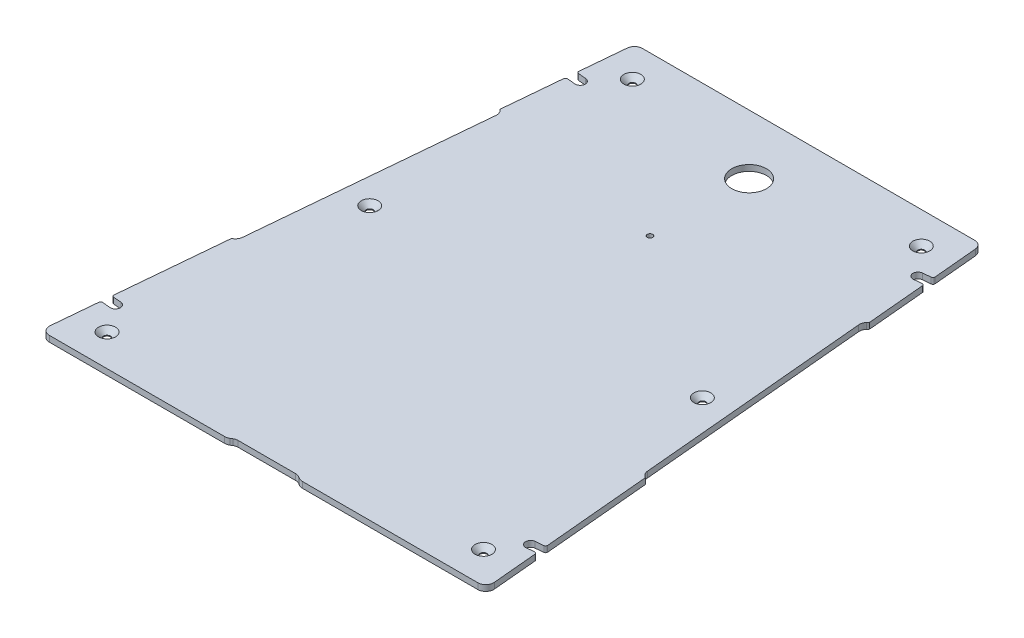
SolidWorks part; units mm, degrees
ref_plane "Front Plane" through (0, 0, 0) normal (0, 0, 1) x (1, 0, 0)
ref_plane "Top Plane" through (0, 0, 0) normal (0, 1, 0) x (1, 0, 0)
ref_plane "Right Plane" through (0, 0, 0) normal (1, 0, 0) x (0, 0, -1)
sketch "Sketch1" plane through (0, 0, 0) normal (0, 1, 0) x (1, 0, 0)
  line L0 (-175, 275) -> (-225, -275)
  line L1 (-225, -275) -> (225, -275)
  line L2 (225, -275) -> (175, 275)
  line L3 (175, 275) -> (-175, 275)
  line L4 (0, -275) -> (0, 275) construction
  line L5 (-200, 0) -> (200, 0) construction
  line L6 (-145.7771, 243) -> (-189.9589, -243) construction
  line L7 (-189.9589, -243) -> (189.9589, -243) construction
  line L8 (189.9589, -243) -> (145.7771, 243) construction
  line L9 (145.7771, 243) -> (-145.7771, 243) construction
  circle A0 centre (0, 215) radius 17.5
  circle A1 centre (-145.7771, 243) radius 3.4
  circle A2 centre (145.7771, 243) radius 3.4
  circle A5 centre (-189.9589, -243) radius 3.4
  circle A6 centre (189.9589, -243) radius 3.4
  circle A7 centre (-167.868, 0) radius 3.4
  circle A8 centre (167.868, 0) radius 3.4
  circle A9 centre (0, 115) radius 2.731
  point P8 (0, 0)
  point P12 (0, 0)
  dimension "D3" = 35
  dimension "D5" = 6.8
  dimension "D8" = 6.8
  dimension "D12" = 5.4621
  dimension "D1" = 350
  dimension "D2" = 550
  dimension "D4" = 60
  dimension "D10" = 450
  dimension "D11" = 100
  dimension "D13" = 32
extrude "Boss-Extrude1" add sketch "Sketch1" against normal blind 6
fillet "Fillet1" radius 8 4 edges at (225, -3, 275) (-225, -3, 275) (175, -3, -275) (-175, -3, -275)
extrude "Cut-Extrude4" cut sketch "Sketch5" against normal blind 20
sketch "Sketch5" plane through (0, 0, 377.3339) normal (0, 1, 0) x (0, 0, 1)
  line L0 (-592.3339, 0) -> (-592.3339, 41) construction
  line L1 (-592.3339, 0) -> (-520.1613, 72.1726) construction
  circle A7 centre (-563.3425, 28.9914) radius 3.4
  circle A8 centre (-563.3425, -28.9914) radius 3.4
  circle A9 centre (-621.3253, -28.9914) radius 3.4
  circle A10 centre (-621.3253, 28.9914) radius 3.4
  point P12 (-592.3339, 0)
  point P13 (-539.2171, 0)
  point P14 (-592.3339, 0)
  point P15 (-514.4105, -0.115)
  point P19 (-592.3339, 0)
  dimension "D3" = 6.8
  dimension "D2" = 45
  dimension "D4" = 41
  dimension "D5" = 4
sketch "Sketch6" plane through (0, 0, 0) normal (0, 1, 0) x (1, 0, 0)
  line L0 (0, 275) -> (0, -275) construction
  line L1 (167.6943, 275) -> (-167.6943, 275) construction
  line L2 (-216.2397, -275) -> (216.2397, -275) construction
  line L3 (199.9342, 0.7243) -> (-199.9342, 0.7243) construction
  line L4 (224.2069, -266.2757) -> (175.6614, 267.7243) construction
  line L5 (-175.6614, 267.7243) -> (-224.2069, -266.2757) construction
  line L6 (-204.632, -95.1331) -> (-182.7223, 145.8731)
  line L7 (-204.632, -95.1331) -> (-218.4599, -106.6564)
  line L8 (-182.7223, 145.8731) -> (-194.2456, 159.7011)
  line L9 (-218.4599, -106.6564) -> (-194.2456, 159.7011)
  point P13 (-124.3469, 2.1706)
  dimension "D1" = 18
  dimension "D2" = 242
  dimension "D3" = 135
  dimension "D4" = 4
extrude "Cut-Extrude5" cut sketch "Sketch6" against normal blind 10
sketch "Sketch7" plane through (0, 0, 0) normal (0, 1, 0) x (1, 0, 0)
  line L0 (0, 275) -> (0, -275) construction
  line L1 (167.6943, 275) -> (-167.6943, 275) construction
  line L2 (-216.2397, -275) -> (216.2397, -275) construction
  line L4 (-31.3206, -271.5943) -> (31.3206, -271.5943)
  line L5 (-31.3206, -271.5943) -> (-45, -279.8932)
  line L6 (-45, -279.8932) -> (45, -279.8932)
  line L7 (31.3206, -271.5943) -> (45, -279.8932)
  line L8 (-31.3206, -271.5943) -> (45, -279.8932) construction
  line L9 (-45, -279.8932) -> (31.3206, -271.5943) construction
  dimension "D1" = 90
  dimension "D2" = 16
extrude "Cut-Extrude6" cut sketch "Sketch7" against normal blind 10
mirror "Mirror2" about plane through (0, 0, 0) normal (1, 0, 0) of "Cut-Extrude5"
fillet "Fillet2" radius 8 8 edges at (-204.632, -3, 95.1331) (-182.7223, -3, -145.8731) (-36.9344, -3, 275) (-31.3206, -3, 271.5943) (36.9344, -3, 275) (31.3206, -3, 271.5943) (204.632, -3, 95.1331) (182.7223, -3, -145.8731)
chamfer "Chamfer1" distance 5.15 angle 45 6 edges at (-145.7771, 0, -239.6) (189.9589, 0, 239.6) (167.868, 0, -3.4) (-189.9589, 0, 246.4) (-167.868, 0, 3.4) (145.7771, 0, -246.4)
sketch "Sketch9" plane through (0, 0, 0) normal (0, 1, 0) x (1, 0, 0)
  line L0 (0, 275) -> (0, -271.5943) construction
  line L1 (167.6943, 275) -> (-167.6943, 275) construction
  line L2 (29.0836, -271.5943) -> (-29.0836, -271.5943) construction
  line L3 (-193.6771, 25.37) -> (193.6771, 25.37) construction
  line L4 (-204.332, -91.833) -> (-183.0223, 142.573) construction
  line L5 (204.332, -91.833) -> (183.0223, 142.573) construction
  line L6 (-148.0781, 29.9183) -> (-163.4505, -139.1782)
  line L7 (-200.9499, -54.63) -> (200.9499, -54.63) construction
  line L8 (-123.1808, 52.6549) -> (123.1808, 52.6549)
  line L9 (-138.5532, -166.4416) -> (138.5532, -166.4416)
  line L10 (148.0781, 29.9183) -> (163.4505, -139.1782)
  arc A0 (-163.4505, -139.1782) -> (-138.5532, -166.4416) centre (-138.5532, -141.4416) ccw
  arc A1 (-148.0781, 29.9183) -> (-123.1808, 52.6549) centre (-123.1808, 27.6549) cw
  arc A2 (163.4505, -139.1782) -> (138.5532, -166.4416) centre (138.5532, -141.4416) cw
  arc A3 (148.0781, 29.9183) -> (123.1808, 52.6549) centre (123.1808, 27.6549) ccw
  point P14 (-155.7643, -54.63)
  point P21 (-165.929, -166.4416)
  point P24 (-146.0111, 52.6549)
  point P28 (0, -166.4416)
  point P31 (0, 52.6549)
  dimension "D4" = 25
  dimension "D1" = 45
  dimension "D2" = 80
  dimension "D3" = 220
sketch "Sketch10" [suppressed] plane through (0, 0, 94.4754) normal (0, 0, 1) x (1, 0, 0)
  line L0 (-89.3279, 30) -> (-81.3279, 30)
  line L1 (-144.5624, 30) -> (-37.7732, 30) construction
  arc A0 (-89.3279, 30) -> (-81.3279, 30) centre (-85.3279, 33) ccw
  point P5 (-85.3279, 30)
  dimension "D1" = 10
sweep "Cut-Sweep2" [suppressed] cut profiles "Sketch10" path "Sketch9"
sketch "Sketch11" plane through (0, 0, 0) normal (0, 1, 0) x (1, 0, 0)
  line L3 (167.6943, 275) -> (-167.6943, 275) construction
  line L4 (-179.9105, 220.9844) -> (-169.9516, 220.0791)
  line L5 (-219.0014, -209.0156) -> (-209.0425, -209.9209)
  line L6 (-219.9249, -219.1737) -> (-209.9659, -220.0791)
  line L7 (-175.6614, 267.7243) -> (-186.3437, 150.2188) construction
  line L8 (-180.834, 210.8263) -> (-170.875, 209.9209)
  line L9 (-179.9105, 220.9844) -> (-180.834, 210.8263)
  line L10 (-219.0014, -209.0156) -> (-219.9249, -219.1737)
  line L11 (-208.9777, -98.7545) -> (-224.2069, -266.2757) construction
  line L12 (-216.2397, -275) -> (-39.1713, -275) construction
  line L13 (0, -3.3) -> (0, 3.3) construction
  line L14 (219.0014, -209.0156) -> (219.9249, -219.1737)
  line L15 (179.9105, 220.9844) -> (180.834, 210.8263)
  line L16 (180.834, 210.8263) -> (170.875, 209.9209)
  line L17 (219.9249, -219.1737) -> (209.9659, -220.0791)
  line L18 (219.0014, -209.0156) -> (209.0425, -209.9209)
  line L19 (179.9105, 220.9844) -> (169.9516, 220.0791)
  arc A1 (-170.875, 209.9209) -> (-169.9516, 220.0791) centre (-170.4133, 215) ccw
  arc A3 (-209.9659, -220.0791) -> (-209.0425, -209.9209) centre (-209.5042, -215) ccw
  arc A4 (209.9659, -220.0791) -> (209.0425, -209.9209) centre (209.5042, -215) cw
  arc A5 (170.875, 209.9209) -> (169.9516, 220.0791) centre (170.4133, 215) cw
  dimension "D1" = 5.1
  dimension "D4" = 10
  dimension "D2" = 10
  dimension "D3" = 60
  dimension "D5" = 60
extrude "Cut-Extrude7" cut sketch "Sketch11" against normal blind 10
fillet "Fillet3" radius 2 8 edges at (180.834, -3, -210.8263) (179.9105, -3, -220.9844) (219.0014, -3, 209.0156) (219.9249, -3, 219.1737) (-219.9249, -3, 219.1737) (-219.0014, -3, 209.0156) (-180.834, -3, -210.8263) (-179.9105, -3, -220.9844)
sketch "Sketch12" plane through (0, 0, 0) normal (0, 1, 0) x (1, 0, 0)
  line L0 (75, 275) -> (75, 155) construction
  line L1 (167.6943, 275) -> (-167.6943, 275) construction
  line L3 (0, -3.3) -> (0, 3.3) construction
  circle A0 centre (75, 175) radius 2.6
  circle A1 centre (75, 155) radius 2.6
  dimension "D1" = 5.2
  dimension "D2" = 20
  dimension "D3" = 100
  dimension "D4" = 75
extrude "Cut-Extrude8" [suppressed] cut sketch "Sketch12" against normal up to next
chamfer "Chamfer2" [suppressed] distance 3 angle 30
